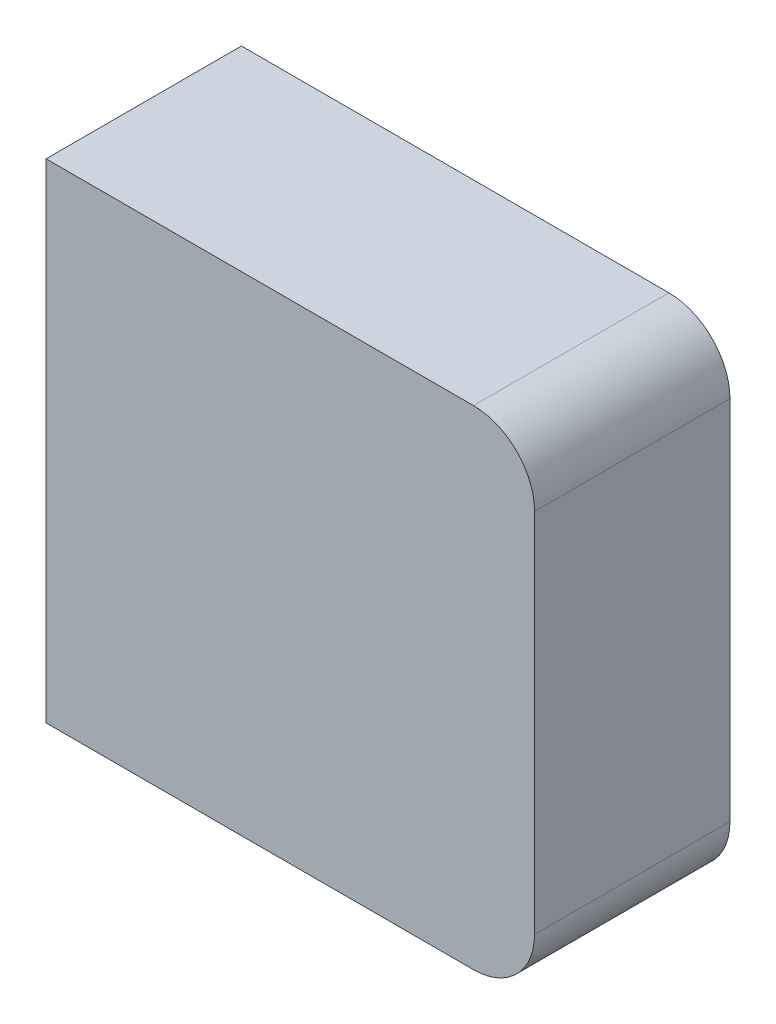
SolidWorks part; units mm, degrees
material "1060 Alloy"
ref_plane "Front Plane" through (0, 0, 0) normal (0, 0, 1) x (1, 0, 0)
ref_plane "Top Plane" through (0, 0, 0) normal (0, 1, 0) x (1, 0, 0)
ref_plane "Right Plane" through (0, 0, 0) normal (1, 0, 0) x (0, 0, -1)
sketch "Sketch2" plane through (0, 0, 0) normal (0, 0, 1) x (1, 0, 0)
  line L1 (10, -10) -> (-10, -10)
  line L2 (10, -10) -> (10, 10)
  line L3 (10, 10) -> (-10, 10)
  line L4 (-10, -10) -> (-10, 10)
  line L5 (10, -10) -> (-10, 10) construction
  line L6 (10, 10) -> (-10, -10) construction
  point P0 (0, 0)
  dimension "D1" = 20
  dimension "D2" = 20
extrude "Boss-Extrude1" add sketch "Sketch2" along normal mid plane 8
fillet "Fillet1" radius 2.5 2 edges at (10, -10, 0) (10, 10, 0)
hole_wizard "Tapped Hole for M4x0.7 Helicoil1" positions "Sketch3" profile "Sketch4" tap size "M4x0.7" standard "Helicoil® Metric"
sketch "Sketch3" plane through (-10, 0, 0) normal (-1, 0, 0) x (0, 0, 1)
  line L0 (0, -5) -> (0, 5) construction
  point P0 (0, 5)
  point P2 (0, -5)
  dimension "D1" = 10
sketch "Sketch4" plane through (-10, 5, 0) normal (0, 1, 0) x (0, 0, 1)
  line L0 (0, 0) -> (0, 8.0618)
  line L1 (0, 8.0618) -> (2.1, 6.8)
  line L2 (2.1, 6.8) -> (2.1, 0)
  line L5 (2.1, 0) -> (0, 0)
  line L10 (0, 8.0618) -> (-2.1, 6.8) construction
  line L11 (0, -6.35) -> (0, 107.95) construction
  dimension "Tap Drill Dia." = 4.2
  dimension "Tap Drill Depth" = 6.8
  dimension "Drill Angle" = 118
cosmetic thread "Hole Thread1"
cosmetic thread "Hole Thread2"
